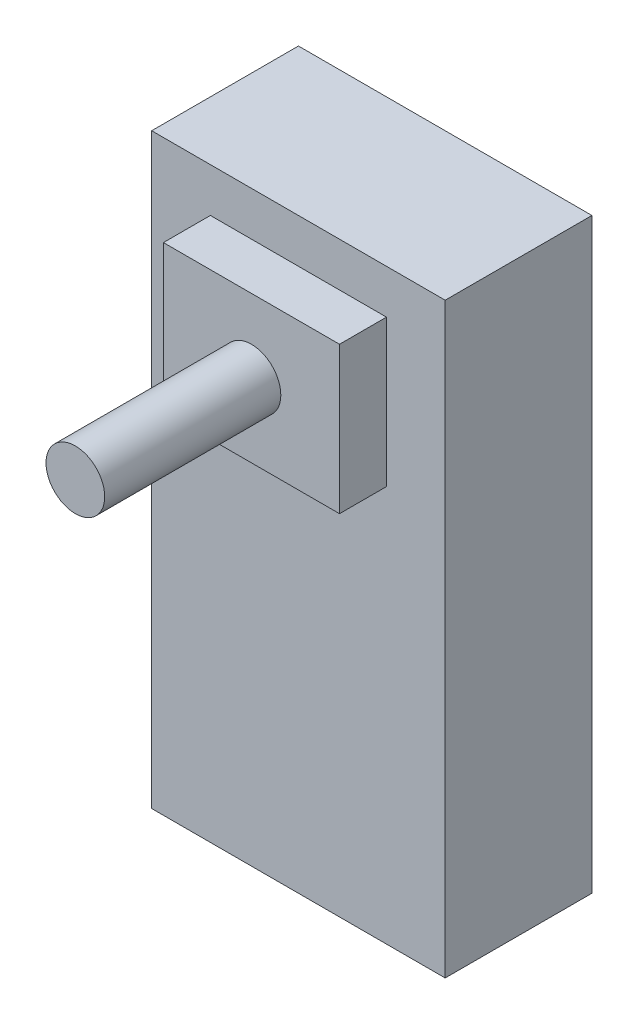
SolidWorks part; units mm, degrees
ref_plane "Front Plane" through (0, 0, 0) normal (0, 0, 1) x (1, 0, 0)
ref_plane "Top Plane" through (0, 0, 0) normal (0, 1, 0) x (1, 0, 0)
ref_plane "Right Plane" through (0, 0, 0) normal (1, 0, 0) x (0, 0, -1)
sketch "Sketch2" plane through (0, 0, 0) normal (0, 0, 1) x (1, 0, 0)
  line L1 (-25, -50) -> (25, -50)
  line L2 (-25, -50) -> (-25, 50)
  line L3 (-25, 50) -> (25, 50)
  line L4 (25, -50) -> (25, 50)
  point P0 (0, 0)
  dimension "D1" = 50
  dimension "D2" = 100
extrude "Boss-Extrude1" add sketch "Sketch2" against normal blind 25
sketch "Sketch5" plane through (0, 0, 0) normal (0, 0, 1) x (1, 0, 0)
  line L0 (25, -50) -> (25, 50) construction
  line L1 (-15, 42.5) -> (15, 42.5)
  line L2 (-15, 42.5) -> (-15, 17.5)
  line L3 (-15, 17.5) -> (15, 17.5)
  line L4 (15, 42.5) -> (15, 17.5)
  point P0 (0, 30)
  dimension "D1" = 30
  dimension "D2" = 25
  dimension "D3" = 30
  dimension "D4" = 25
extrude "Boss-Extrude3" add sketch "Sketch5" along normal blind 8
sketch "Sketch6" plane through (0, 0, 8) normal (0, 0, 1) x (1, 0, 0)
  line L2 (-15, 17.5) -> (15, 17.5) construction
  circle A0 centre (0, 30) radius 5
  dimension "D1" = 10
  dimension "D2" = 12.5
extrude "Boss-Extrude4" add sketch "Sketch6" along normal blind 30
